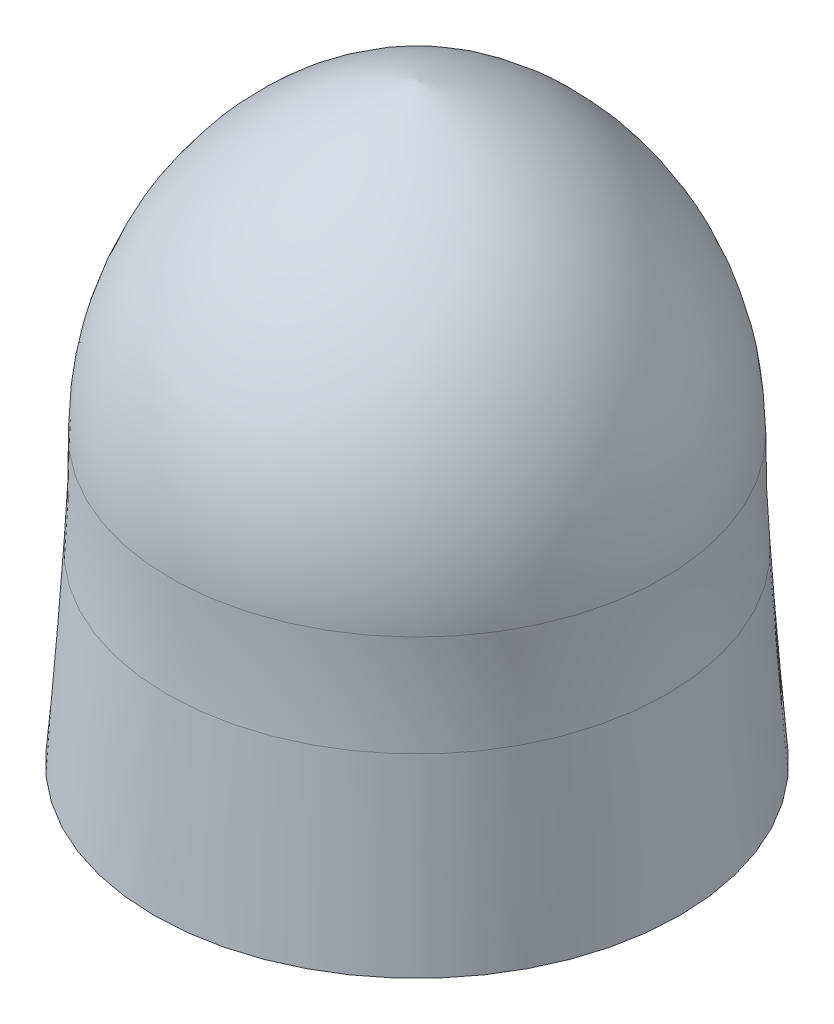
SolidWorks part; units mm, degrees
ref_plane "Front Plane" through (0, 0, 0) normal (0, 0, 1) x (1, 0, 0)
ref_plane "Top Plane" through (0, 0, 0) normal (0, 1, 0) x (1, 0, 0)
ref_plane "Right Plane" through (0, 0, 0) normal (1, 0, 0) x (0, 0, -1)
sketch "Sketch1" plane through (0, 0, 0) normal (0, 0, 1) x (1, 0, 0)
  line L0 (0, 0) -> (0, -90) construction
  line L1 (-37.2972, -51.3476) -> (-40, -90)
  line L2 (-40, -90) -> (0, -90)
  line L3 (0, 0) -> (0, -90)
  arc A0 (0, 0) -> (-37.2972, -51.3476) centre (10, -46.4832) ccw
  dimension "D1" = 10
  dimension "D2" = 4
  dimension "D3" = 40
  dimension "D4" = 90
revolve "Revolve2" add sketch "Sketch1" angle 360 about L0
fillet "Fillet1" radius 200 1 edges at (-37.2972, -51.3476, 0)
